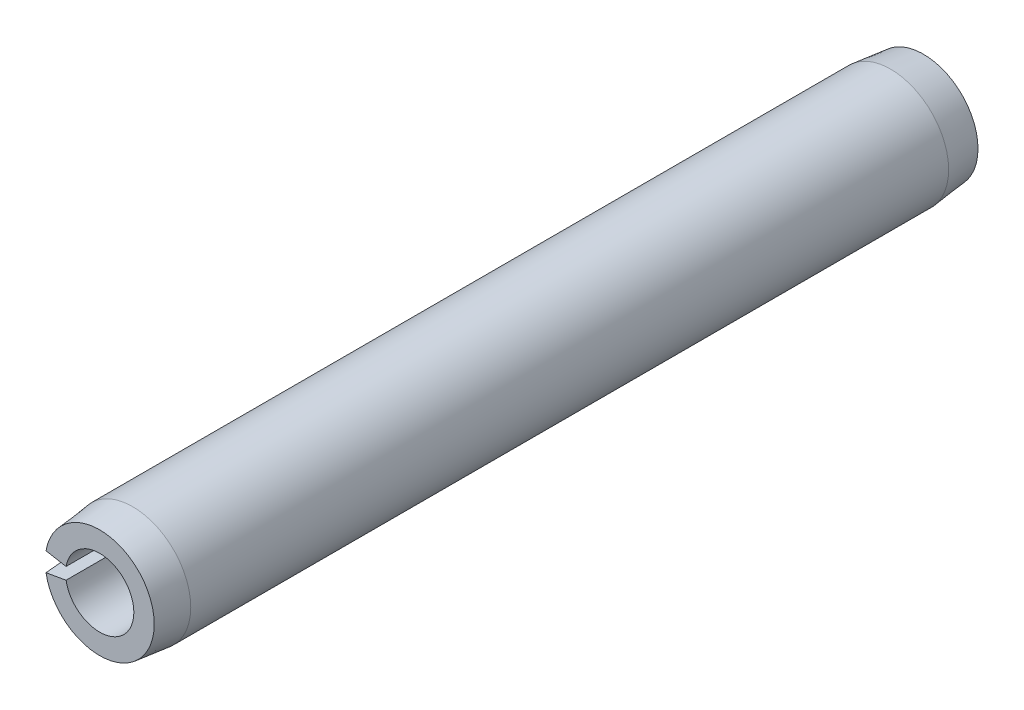
SolidWorks part; units mm, degrees
material "AISI 1045 Steel, cold drawn"
ref_plane "Front Plane" through (0, 0, 0) normal (0, 0, 1) x (1, 0, 0)
ref_plane "Top Plane" through (0, 0, 0) normal (0, 1, 0) x (1, 0, 0)
ref_plane "Right Plane" through (0, 0, 0) normal (1, 0, 0) x (0, 0, -1)
sketch "Sketch5" plane through (0, 0, 0) normal (0, 0, 1) x (1, 0, 0)
  line L0 (1.4478, 0) -> (2.4638, 0) construction
  line L1 (-2.4264, 0.4278) -> (-1.4258, 0.2514)
  line L2 (-1.4258, -0.2514) -> (-2.4264, -0.4278)
  arc A0 (-2.4264, -0.4278) -> (-2.4264, 0.4278) centre (0, 0) ccw
  arc A1 (-1.4258, -0.2514) -> (-1.4258, 0.2514) centre (0, 0) ccw
  dimension "Diameter" = 4.9276
  dimension "Wall Thickness" = 1.016
  dimension "D3" = 20
sketch "Sketch6" plane through (0, 0, 0) normal (1, 0, 0) x (0, 0, -1)
  line L0 (17.4625, 0) -> (-17.4625, 0) construction
  line L1 (0, 2.4638) -> (0, -2.4638) construction
  line L4 (0, 2.4638) -> (0, -2.4638) construction
  line L5 (17.4625, 0) -> (17.4625, 2.4638) construction
  line L6 (17.4625, 2.4638) -> (-17.4625, 2.4638) construction
  line L7 (-17.4625, 2.4638) -> (-17.4625, 0) construction
  line L8 (17.4625, 2.3114) -> (16.0655, 2.4638)
  dimension "Length" = 34.925
  dimension "Chamfer" = 1.397
  dimension "Chamfer Dia." = 4.6228
sketch "Sketch1" plane through (0, 0, 0) normal (0, 0, 1) x (1, 0, 0)
  line L1 (-1.4258, -0.2514) -> (-2.4264, -0.4278) construction
  line L2 (-2.4264, 0.4278) -> (-1.4258, 0.2514) construction
  line L3 (-1.4258, -0.2514) -> (-2.4264, -0.4278)
  line L4 (-2.4264, 0.4278) -> (-1.4258, 0.2514)
  arc A2 (-2.4264, -0.4278) -> (-2.4264, 0.4278) centre (0, 0) ccw construction
  arc A3 (-1.4258, -0.2514) -> (-1.4258, 0.2514) centre (0, 0) ccw construction
  arc A4 (-2.4264, -0.4278) -> (-2.4264, 0.4278) centre (0, 0) ccw
  arc A5 (-1.4258, -0.2514) -> (-1.4258, 0.2514) centre (0, 0) ccw
extrude "Extrude1" add sketch "Sketch1" against normal up to vertex (17.4625 mm away) and the other way up to vertex (17.4625 mm away) up to point (0, 2.4638, -17.4625) other way up to point (0, 2.4638, 17.4625)
sketch "Sketch2" plane through (0, 0, 0) normal (1, 0, 0) x (0, 0, -1)
  line L0 (17.4625, 2.3114) -> (16.0655, 2.4638)
  line L1 (16.0655, 2.4638) -> (17.4625, 2.4638)
  line L4 (17.4625, 2.4638) -> (17.4625, 2.3114)
revolve "Cut-Revolve1" cut sketch "Sketch2" angle 360 about L0
mirror "Mirror1" about plane through (0, 0, 0) normal (0, 0, 1) of "Cut-Revolve1"
sketch "Sketch3" plane through (0, 0, 0) normal (0, 0, 1) x (1, 0, 0)
  line L1 (1.4478, 0) -> (2.4638, 0)
  circle A0 centre (0, 0) radius 1.4478
  circle A1 centre (0, 0) radius 2.4638
